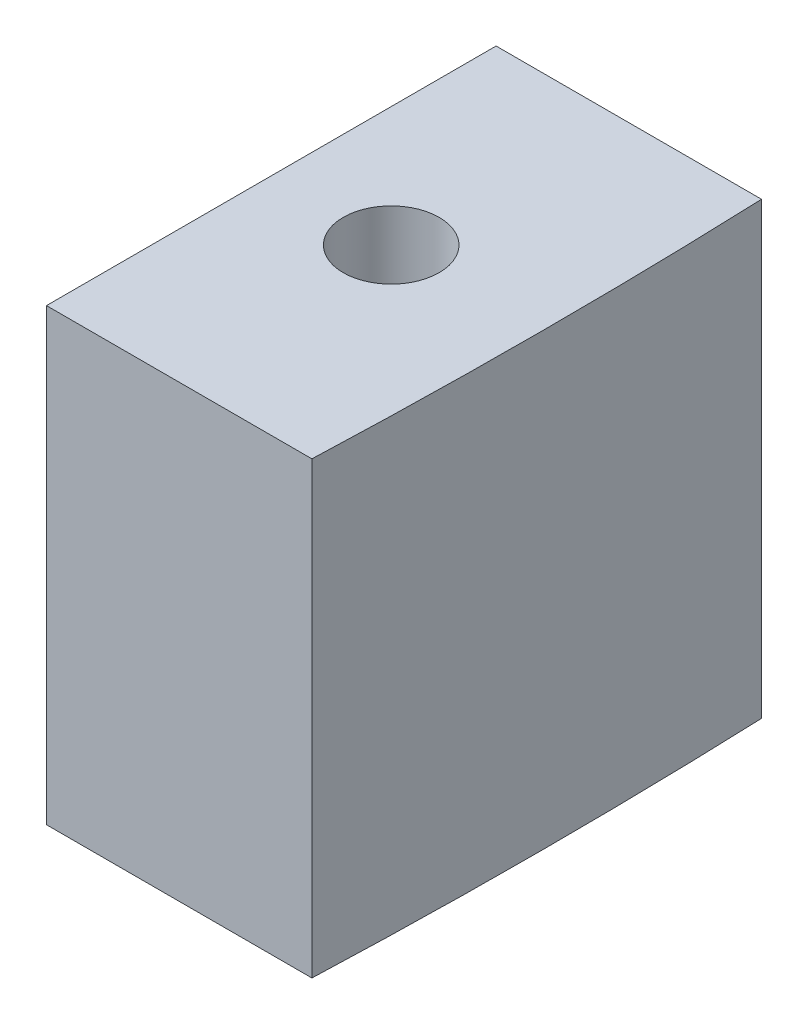
SolidWorks part; units mm, degrees
ref_plane "前视基准面" through (0, 0, 0) normal (0, 0, 1) x (1, 0, 0)
ref_plane "上视基准面" through (0, 0, 0) normal (0, 1, 0) x (1, 0, 0)
ref_plane "右视基准面" through (0, 0, 0) normal (1, 0, 0) x (0, 0, -1)
sketch "草图1" plane through (0, 0, 0) normal (0, 1, 0) x (1, 0, 0)
  line L1 (-33.4485, 7.5) -> (33.4485, 7.5)
  line L2 (-33.4485, 7.5) -> (-33.4485, -7.5)
  line L3 (-33.4485, -7.5) -> (33.4485, -7.5)
  line L4 (33.4485, 7.5) -> (33.4485, -7.5)
  line L5 (-33.4485, 7.5) -> (33.4485, -7.5) construction
  line L6 (-33.4485, -7.5) -> (33.4485, 7.5) construction
  point P0 (0, 0)
  dimension "D1" = 15
extrude "凸台-拉伸1" add sketch "草图1" along normal blind 15
sketch "草图2" plane through (0, 0, 0) normal (0, -1, 0) x (1, 0, 0)
  line L0 (-24.5936, 7.5) -> (33.4485, 7.5)
  line L1 (33.4485, 7.5) -> (33.4485, -7.5)
  line L2 (33.4485, -7.5) -> (-24.5936, -7.5)
  line L5 (33.4485, -7.5) -> (-33.4485, -7.5) construction
  line L6 (-33.4485, 7.5) -> (33.4485, 7.5) construction
  arc A0 (-24.5936, -7.5) -> (-24.5936, 7.5) centre (-218.4485, 0) ccw
extrude "切除-拉伸1" cut sketch "草图2" against normal up to next
hole_wizard "M3 间隙孔1" positions "草图3" profile "草图4" hole size "M3" standard "ISO" end condition up to next
sketch "草图3" plane through (0, 0, 0) normal (0, -1, 0) x (-1, 0, 0)
  line L1 (-4.95, 0) -> (4.95, 0) construction
  line L2 (33.4485, 7.5) -> (33.4485, -7.5) construction
  point P0 (29.4485, 0)
  dimension "D1" = 4
sketch "草图4" plane through (-29.4485, 0, 0) normal (1, 0, 0) x (0, 0, -1)
  line L0 (0, 0) -> (0, 15)
  line L1 (0, 15) -> (1.6, 15)
  line L2 (1.6, 15) -> (1.6, 0)
  line L5 (1.6, 0) -> (0, 0)
  line L11 (0, -6.35) -> (0, 107.95) construction
  dimension "通孔孔直径" = 3.2
  dimension "通孔孔深度" = 15
sketch "草图5" plane through (0, 0, 0) normal (0, -1, 0) x (1, 0, 0)
  line L1 (-29.4485, -3.3486) -> (-26.5485, -1.6743)
  line L2 (-26.5485, -1.6743) -> (-26.5485, 1.6743)
  line L3 (-26.5485, 1.6743) -> (-29.4485, 3.3486)
  line L4 (-29.4485, 3.3486) -> (-32.3485, 1.6743)
  line L5 (-32.3485, 1.6743) -> (-32.3485, -1.6743)
  line L6 (-32.3485, -1.6743) -> (-29.4485, -3.3486)
  circle A0 centre (-29.4485, 0) radius 2.9 construction
  dimension "D1" = 5.8
extrude "切除-拉伸2" cut sketch "草图5" against normal blind 4
